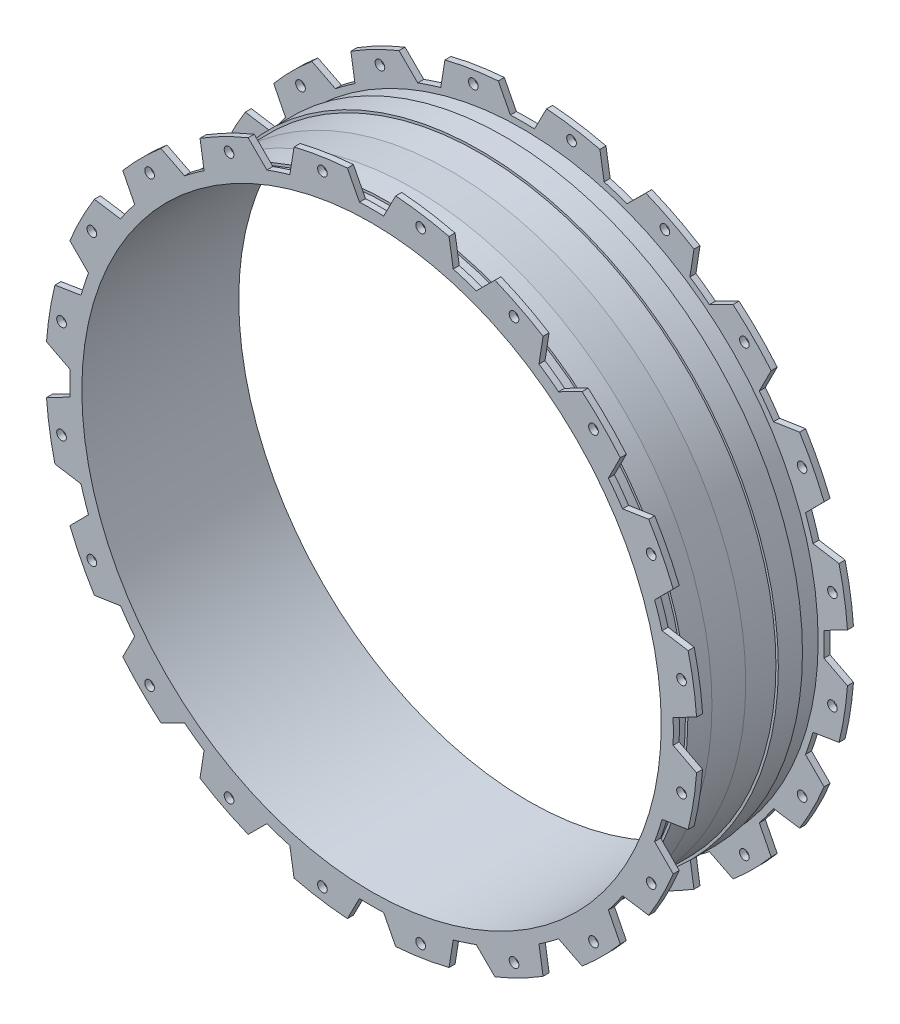
SolidWorks part; units mm, degrees
ref_plane "Front Plane" through (0, 0, 0) normal (0, 0, 1) x (1, 0, 0)
ref_plane "Top Plane" through (0, 0, 0) normal (0, 1, 0) x (1, 0, 0)
ref_plane "Right Plane" through (0, 0, 0) normal (1, 0, 0) x (0, 0, -1)
sketch "Sketch1" plane through (0, 0, 0) normal (1, 0, 0) x (0, 0, -1)
  line L0 (-71.0938, 0) -> (89.6875, 0) construction
  line L1 (65, 240) -> (65, 270)
  line L2 (65, 270) -> (60, 270)
  line L3 (60, 270) -> (60, 245)
  line L4 (60, 245) -> (45, 245)
  line L5 (45, 245) -> (45, 247)
  line L6 (45, 247) -> (25, 247)
  line L7 (25, 247) -> (25, 245)
  line L8 (25, 245) -> (0, 245)
  line L9 (0, 245) -> (-30, 247)
  line L10 (-30, 247) -> (-50, 247)
  line L11 (-50, 247) -> (-50, 245)
  line L12 (-50, 245) -> (-60, 245)
  line L13 (-60, 245) -> (-60, 270)
  line L14 (-60, 270) -> (-65, 270)
  line L15 (-65, 270) -> (-65, 240)
  line L16 (-65, 240) -> (65, 240)
  point P11 (0, 240)
  point P20 (0, 0)
  point P21 (0, 0)
  dimension "D1" = 5
  dimension "D2" = 10
  dimension "D3" = 20
  dimension "D4" = 30
  dimension "D5" = 25
  dimension "D6" = 20
  dimension "D7" = 15
  dimension "D8" = 5
  dimension "D9" = 2
  dimension "D10" = 5
  dimension "D11" = 2
  dimension "D12" = 240
  dimension "D13" = 270
revolve "Revolve1" add sketch "Sketch1" angle 360 about L0
sketch "Sketch2" plane through (0, 0, 65) normal (0, 0, 1) x (1, 0, 0)
  line L0 (0, 250) -> (0, 270) construction
  line L1 (10, 249.7999) -> (20, 269.2582)
  line L2 (-10, 249.7999) -> (-20, 269.2582)
  circle A0 centre (0, 0) radius 270 construction
  arc A1 (10, 249.7999) -> (-10, 249.7999) centre (0, 0) ccw
  arc A2 (-20, 269.2582) -> (20, 269.2582) centre (0, 0) cw
  dimension "D1" = 500
  dimension "D2" = 20
  dimension "D3" = 10
extrude "Cut-Extrude1" cut sketch "Sketch2" against normal through all
pattern_circular "CirPattern1" count 20 over 360 about axis through (0, 0, 0) along (0, 0, 1) of "Cut-Extrude1"
sketch "Sketch3" plane through (0, 0, 65) normal (0, 0, 1) x (1, 0, 0)
  line L0 (0, 0) -> (42.2373, 266.6759) construction
  circle A0 centre (40.673, 256.799) radius 4
  arc A1 (64.1842, 262.2601) -> (20, 269.2582) centre (0, 0) ccw construction
  point P8 (0, 0)
  dimension "D1" = 8
  dimension "D2" = 260
extrude "Cut-Extrude2" cut sketch "Sketch3" against normal through all
pattern_circular "CirPattern2" count 20 over 360 about axis through (0, 0, 0) along (0, 0, 1) of "Cut-Extrude2"
